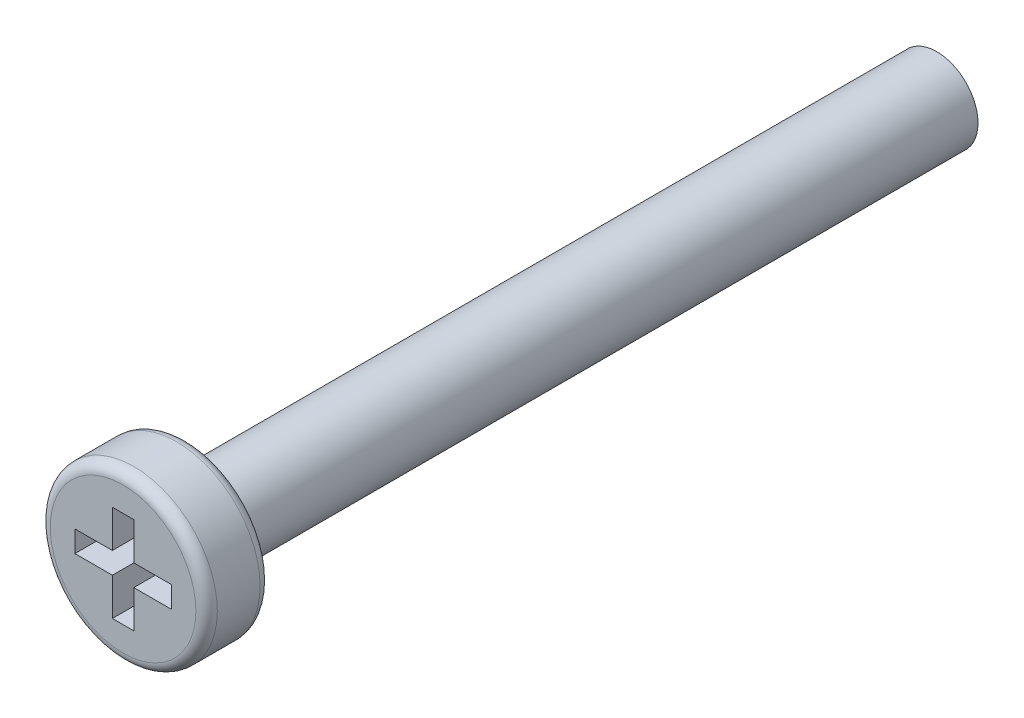
SolidWorks part; units mm, degrees
ref_plane "Plano frontal" through (0, 0, 0) normal (0, 0, 1) x (1, 0, 0)
ref_plane "Plano superior" through (0, 0, 0) normal (0, 1, 0) x (1, 0, 0)
ref_plane "Plano direito" through (0, 0, 0) normal (1, 0, 0) x (0, 0, -1)
sketch "Esboço5" plane through (0, 0, 0) normal (0, 0, 1) x (1, 0, 0)
  circle A0 centre (0, 0) radius 3.9
  dimension "D1" = 7.8
extrude "Ressalto-extrusão2" add sketch "Esboço5" along normal blind 3
sketch "Esboço7" plane through (0, 0, 3) normal (0, 0, 1) x (1, 0, 0)
  line L0 (-0.5, -0.5) -> (-2.25, -0.5)
  line L1 (0.5, 2.25) -> (-0.5, 2.25)
  line L2 (0.5, 2.25) -> (0.5, 0.5)
  line L3 (0.5, -2.25) -> (-0.5, -2.25)
  line L4 (-0.5, 2.25) -> (-0.5, 0.5)
  line L7 (2.25, 0.5) -> (0.5, 0.5)
  line L8 (2.25, 0.5) -> (2.25, -0.5)
  line L9 (2.25, -0.5) -> (0.5, -0.5)
  line L10 (-2.25, 0.5) -> (-2.25, -0.5)
  line L13 (-0.5, -0.5) -> (-0.5, -2.25)
  line L15 (-0.5, 0.5) -> (-2.25, 0.5)
  line L18 (0.5, -0.5) -> (0.5, -2.25)
  point P0 (0, 0)
  point P5 (0, 0)
extrude "Corte-extrusão3" cut sketch "Esboço7" against normal blind 2
fillet "Filete1" radius 0.5 2 edges at (3.9, 0, 0) (3.9, 0, 3)
sketch "Esboço8" plane through (0, 0, 0) normal (0, 0, -1) x (-1, 0, 0)
  circle A0 centre (0, 0) radius 1.925
  dimension "D1" = 3.85
extrude "Ressalto-extrusão3" add sketch "Esboço8" along normal blind 35
